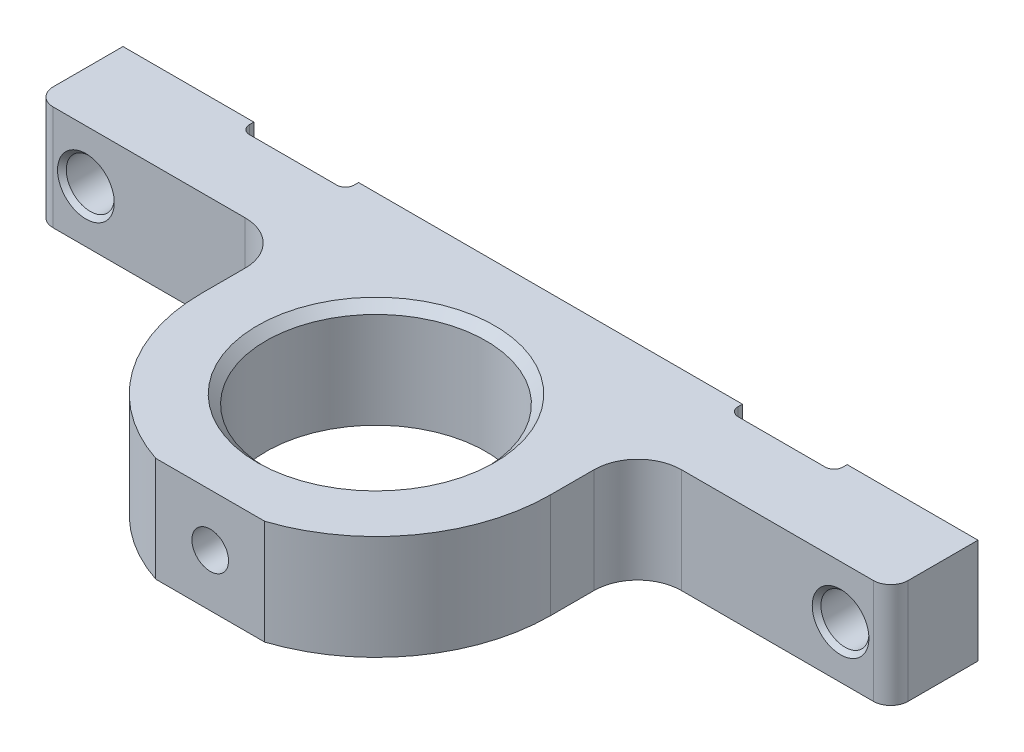
SolidWorks part; units mm, degrees
material "6061 Alloy"
ref_plane "Front Plane" through (0, 0, 0) normal (0, 0, 1) x (1, 0, 0)
ref_plane "Top Plane" through (0, 0, 0) normal (0, 1, 0) x (1, 0, 0)
ref_plane "Right Plane" through (0, 0, 0) normal (1, 0, 0) x (0, 0, -1)
sketch "Sketch1" plane through (0, 0, 0) normal (0, 1, 0) x (1, 0, 0)
  line L0 (-49, 20) -> (-34, 20)
  line L1 (49, 20) -> (49, 10)
  line L2 (49, 10) -> (20, 10)
  line L3 (-49, 20) -> (-49, 10)
  line L4 (-49, 10) -> (-20, 10)
  line L5 (0, 26.6909) -> (0, -48.9961) construction
  line L6 (-20, 0) -> (-20, 10)
  line L7 (20, 0) -> (20, 10)
  line L8 (-6.245, -19) -> (6.245, -19)
  line L9 (-34, 20) -> (-34, 18.5)
  line L10 (-34, 18.5) -> (-22, 18.5)
  line L11 (-22, 18.5) -> (-22, 20)
  line L12 (22, 20) -> (22, 18.5)
  line L13 (22, 18.5) -> (34, 18.5)
  line L14 (34, 18.5) -> (34, 20)
  line L15 (-22, 20) -> (22, 20)
  line L16 (34, 20) -> (49, 20)
  circle A0 centre (0, 0) radius 12.6
  arc A1 (-20, 0) -> (-6.245, -19) centre (0, 0) ccw
  arc A2 (6.245, -19) -> (20, 0) centre (0, 0) ccw
  dimension "D1" = 25.2
  dimension "D5" = 20
  dimension "D2" = 98
  dimension "D3" = 49
  dimension "D4" = 20
  dimension "D6" = 19
  dimension "D7" = 10
  dimension "D8" = 10
  dimension "D9" = 15
  dimension "D10" = 12
  dimension "D11" = 1.5
  dimension "D12" = 15
  dimension "D13" = 12
  dimension "D14" = 1.5
extrude "Boss-Extrude1" add sketch "Sketch1" along normal blind 12
fillet "Fillet1" radius 5 2 edges at (20, 6, -10) (-20, 6, -10)
fillet "Fillet2" radius 2 2 edges at (49, 6, -10) (-49, 6, -10)
hole_wizard "Ø5.5 (5.5) Diameter Hole1" positions "Sketch3" profile "Sketch2" hole size "Ø5.5" standard "ISO" end condition up to next
sketch "Sketch3" plane through (0, 0, -10) normal (0, 0, 1) x (1, 0, 0)
  line L2 (0, 18.2613) -> (0, -14.5188) construction
  point P1 (-43.25, 6)
  point P3 (43.25, 6)
  dimension "D1" = 86.5
  dimension "D2" = 43.25
sketch "Sketch2" plane through (-43.25, 6, -10) normal (1, 0, 0) x (0, -1, 0)
  line L0 (0, 0) -> (0, 10)
  line L1 (0, 10) -> (2.75, 10)
  line L2 (2.75, 10) -> (2.75, 0)
  line L5 (2.75, 0) -> (0, 0)
  line L11 (0, -6.35) -> (0, 107.95) construction
  dimension "Thru Hole Dia." = 5.5
  dimension "Thru Hole Depth" = 10
fillet "Fillet3" radius 1 4 edges at (34, 6, -18.5) (22, 6, -18.5) (-34, 6, -18.5) (-22, 6, -18.5)
hole_wizard "M5 Tapped Hole1" positions "Sketch5" profile "Sketch4" tap size "M5" standard "ISO"
sketch "Sketch5" plane through (0, 0, 19) normal (0, 0, 1) x (1, 0, 0)
  line L0 (0, 13.045) -> (0, -2.8327) construction
  line L3 (-8.5759, 6) -> (9.4015, 6) construction
  point P14 (0, 6)
sketch "Sketch4" plane through (0, 6, 19) normal (1, 0, 0) x (0, -1, 0)
  line L0 (0, 0) -> (0, 6.4)
  line L1 (0, 6.4) -> (2.1, 6.4)
  line L2 (2.1, 6.4) -> (2.1, 0)
  line L5 (2.1, 0) -> (0, 0)
  line L11 (0, -6.35) -> (0, 107.95) construction
  dimension "Thru Tap Drill Dia." = 4.2
  dimension "Thru Tap Drill Depth" = 6.4
cosmetic thread "Hole Thread1" parameters "D2"=5
chamfer "Chamfer1" distance 0.5 angle 45 2 edges at (-40.5, 6, -10) (46, 6, -10)
chamfer "Chamfer2" distance 1 angle 45 1 edges at (0, 12, 12.6)
